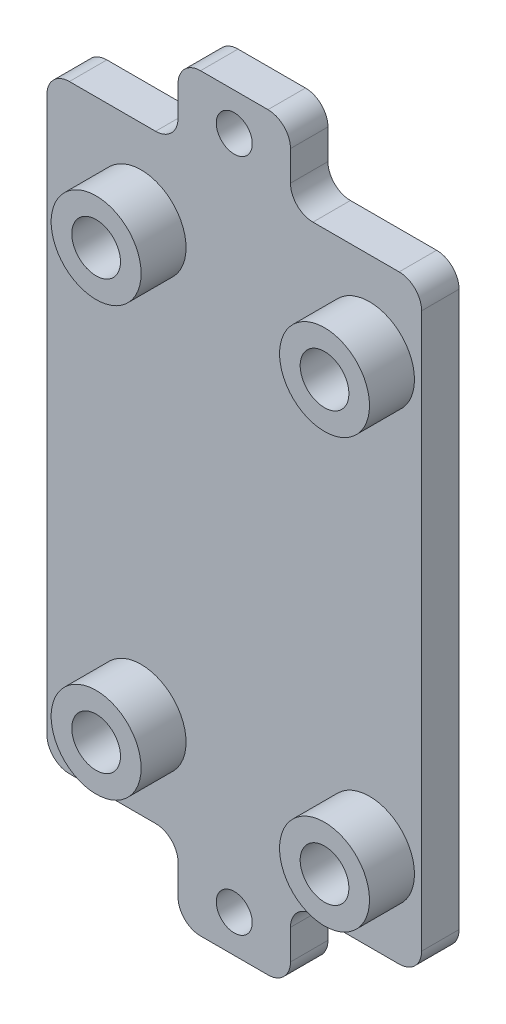
SolidWorks part; units mm, degrees
ref_plane "Front Plane" through (0, 0, 0) normal (0, 0, 1) x (1, 0, 0)
ref_plane "Top Plane" through (0, 0, 0) normal (0, 1, 0) x (1, 0, 0)
ref_plane "Right Plane" through (0, 0, 0) normal (1, 0, 0) x (0, 0, -1)
sketch "Sketch3" plane through (0, 0, 0) normal (0, 0, 1) x (1, 0, 0)
  line L1 (-25, 40) -> (25, 40)
  line L2 (-25, 40) -> (-25, -40)
  line L3 (-25, -40) -> (25, -40)
  line L4 (25, 40) -> (25, -40)
  line L5 (-25, 40) -> (25, -40) construction
  line L6 (-25, -40) -> (25, 40) construction
  point P0 (0, 0)
  dimension "D1" = 80
  dimension "D2" = 50
extrude "Boss-Extrude1" add sketch "Sketch3" along normal blind 5
sketch "Sketch5" plane through (0, 0, 5) normal (0, 0, 1) x (1, 0, 0)
  line L4 (25, -40) -> (25, 40)
  line L5 (25, 40) -> (-25, 40)
  line L6 (-25, 40) -> (-25, -40)
  line L7 (-25, -40) -> (25, -40)
  line L8 (25, -40) -> (25, 40)
  line L9 (25, 40) -> (-25, 40)
  line L10 (-25, 40) -> (-25, -40)
  line L11 (-25, -40) -> (25, -40)
  circle A0 centre (18.046, -28.575) radius 2.1 construction
  circle A1 centre (-12.434, -28.575) radius 2.1 construction
  circle A2 centre (18.046, 28.575) radius 2.1 construction
  circle A3 centre (-12.434, 28.575) radius 2.1 construction
  circle A4 centre (18.046, -28.575) radius 2.1
  circle A5 centre (-12.434, -28.575) radius 2.1
  circle A6 centre (18.046, 28.575) radius 2.1
  circle A7 centre (-12.434, 28.575) radius 2.1
  circle A8 centre (-12.434, -28.575) radius 3.25
  circle A9 centre (18.046, -28.575) radius 3.25
  circle A10 centre (-12.434, 28.575) radius 3.25
  circle A11 centre (18.046, 28.575) radius 3.25
  circle A12 centre (18.046, -28.575) radius 6
  circle A13 centre (-12.434, -28.575) radius 6
  circle A14 centre (-12.434, 28.575) radius 6
  circle A15 centre (18.046, 28.575) radius 6
  dimension "D2" = 6.5
  dimension "D3" = 12
  dimension "D1" = 0
extrude "Boss-Extrude2" add sketch "Sketch5" along normal blind 6 contours A13 A8 | A12 A9 | A14 A10 | A15 A11
sketch "Sketch8" plane through (0, 0, 5) normal (0, 0, 1) x (1, 0, 0)
  line L3 (25, 40) -> (-25, 40) construction
  line L4 (-7.5, 40) -> (7.5, 40)
  line L5 (-7.5, 40) -> (-7.5, 50)
  line L6 (-7.5, 50) -> (7.5, 50)
  line L7 (7.5, 40) -> (7.5, 50)
  line L8 (0, 50) -> (0, 40)
  circle A0 centre (0, 45) radius 2
  point P12 (0, 40)
  line M11 (25, 40) -> (-25, 40)
  dimension "D1" = 4
  dimension "D2" = 15
  dimension "D3" = 10
extrude "Boss-Extrude3" add sketch "Sketch8" against normal blind 5 contours A0 L8 L7 L6 M11 | A0 L8 L6 L5 L4 | L8 A0 | L8 A0
hole_wizard "M4 Clearance Hole1" positions "Sketch11" profile "Sketch10" hole size "M4" standard "ANSI Metric" end condition through all
sketch "Sketch11" plane through (0, 0, 5) normal (0, 0, 1) x (1, 0, 0)
  point P0 (0, 45)
sketch "Sketch10" plane through (0, 45, 5) normal (1, 0, 0) x (0, -1, 0)
  line L0 (0, 0) -> (0, 5)
  line L1 (0, 5) -> (2.4, 5)
  line L2 (2.4, 5) -> (2.4, 0)
  line L5 (2.4, 0) -> (0, 0)
  line L11 (0, -6.35) -> (0, 107.95) construction
  dimension "Thru Hole Dia." = 4.8
  dimension "Thru Hole Depth" = 5
mirror "Mirror1" about plane through (0, 0, 0) normal (0, 1, 0) of "M4 Clearance Hole1", "Boss-Extrude3"
fillet "Fillet1" radius 3 12 edges at (-7.5, 40, 2.5) (-25, 40, 2.5) (-7.5, 50, 2.5) (7.5, 50, 2.5) (7.5, 40, 2.5) (25, 40, 2.5) (25, -40, 2.5) (7.5, -40, 2.5) (7.5, -50, 2.5) (-7.5, -50, 2.5) (-7.5, -40, 2.5) (-25, -40, 2.5)
